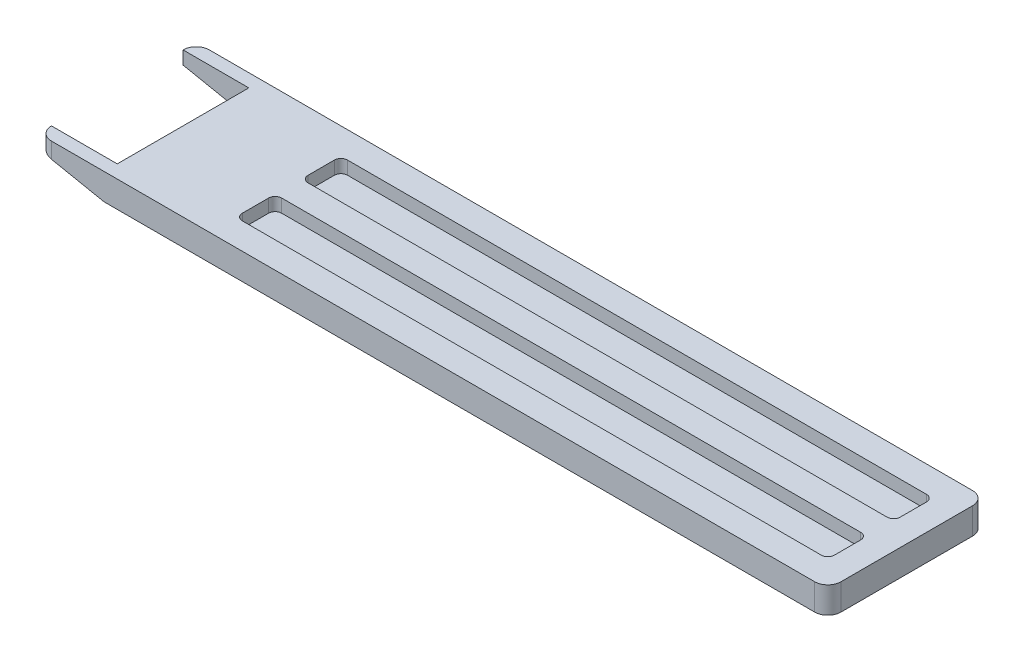
SolidWorks part; units mm, degrees
ref_plane "Front Plane" through (0, 0, 0) normal (0, 0, 1) x (1, 0, 0)
ref_plane "Top Plane" through (0, 0, 0) normal (0, 1, 0) x (1, 0, 0)
ref_plane "Right Plane" through (0, 0, 0) normal (1, 0, 0) x (0, 0, -1)
sketch "Sketch1" plane through (0, 0, 0) normal (0, 1, 0) x (1, 0, 0)
  line L1 (300, -60) -> (-300, -60)
  line L2 (300, -60) -> (300, 60)
  line L3 (300, 60) -> (-300, 60)
  line L4 (-300, -60) -> (-300, 60)
  line L5 (300, -60) -> (-300, 60) construction
  line L6 (300, 60) -> (-300, -60) construction
  point P0 (0, 0)
  dimension "D1" = 120
  dimension "D2" = 600
extrude "Boss-Extrude1" add sketch "Sketch1" along normal blind 20
sketch "Sketch4" plane through (0, 0, 60) normal (0, 0, 1) x (1, 0, 0)
  line L0 (-300, 10) -> (-250, 0)
  line L1 (-300, 20) -> (-300, 0) construction
  line L2 (-300, 0) -> (300, 0) construction
  line L3 (-250, 0) -> (-300, 0)
  line L4 (-300, 0) -> (-300, 10)
  dimension "D1" = 50
extrude "Cut-Extrude1" cut sketch "Sketch4" against normal up to next
sketch "Sketch6" plane through (0, 20, 0) normal (0, 1, 0) x (1, 0, 0)
  line L0 (300, 60) -> (-300, 60) construction
  line L1 (-170, 40) -> (280, 40)
  line L2 (-170, 40) -> (-170, 10)
  line L3 (-170, 10) -> (280, 10)
  line L4 (280, 40) -> (280, 10)
  line L5 (300, -60) -> (300, 60) construction
  line L6 (-300, -60) -> (300, -60) construction
  line L7 (-170, -10) -> (280, -10)
  line L8 (-170, -10) -> (-170, -40)
  line L9 (-170, -40) -> (280, -40)
  line L10 (280, -10) -> (280, -40)
  dimension "D1" = 30
  dimension "D2" = 450
  dimension "D3" = 20
  dimension "D4" = 20
  dimension "D5" = 450
  dimension "D6" = 30
  dimension "D7" = 20
  dimension "D8" = 20
extrude "Cut-Extrude2" cut sketch "Sketch6" against normal blind 10
fillet "Fillet1" radius 10 4 edges at (-300, 15, -60) (-300, 15, 60) (300, 10, -60) (300, 10, 60)
fillet "Fillet2" radius 5 8 edges at (280, 15, 10) (280, 15, 40) (280, 15, -10) (280, 15, -40) (-170, 15, -10) (-170, 15, 40) (-170, 15, -40) (-170, 15, 10)
sketch "Sketch7" plane through (0, 20, 0) normal (0, 1, 0) x (1, 0, 0)
  line L0 (-300, 50) -> (-300, -50) construction
  line L1 (-300, 50) -> (-250, 50)
  line L2 (-300, 50) -> (-300, -50)
  line L3 (-300, -50) -> (-250, -50)
  line L4 (-250, 50) -> (-250, -50)
  line L5 (290, 60) -> (-290, 60) construction
  line L6 (-290, -60) -> (290, -60) construction
  dimension "D1" = 10
  dimension "D2" = 10
  dimension "D3" = 50
extrude "Cut-Extrude3" cut sketch "Sketch7" against normal up to next
equation "\"forklenghth\"=600"
equation "\"D2@Sketch1\"=\"forklenghth\""
equation "\"W_guide\"=30"
equation "\"W_rail\"=30"
equation "\"D1@Sketch6\"=\"W_rail\""
equation "\"L_rail\"=450"
equation "\"D2@Sketch6\"= \"L_rail\""
equation "\"L_rack\"=450"
equation "\"D5@Sketch6\"=\"L_rack\""
equation "\"W_rack\"=30"
equation "\"D6@Sketch6\"=\"W_rack\""
